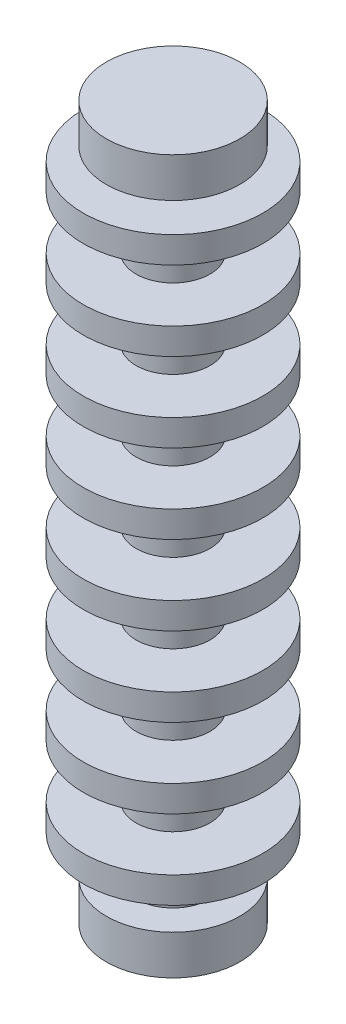
SolidWorks part; units mm, degrees
ref_plane "Front Plane" through (0, 0, 0) normal (0, 0, 1) x (1, 0, 0)
ref_plane "Top Plane" through (0, 0, 0) normal (0, 1, 0) x (1, 0, 0)
ref_plane "Right Plane" through (0, 0, 0) normal (1, 0, 0) x (0, 0, -1)
sketch "Sketch1" plane through (0, 0, 0) normal (0, 0, 1) x (1, 0, 0)
  line L0 (0, -24) -> (0, 24) construction
  line L1 (2.8, 24) -> (2.8, 23)
  line L2 (-20.9325, 24) -> (2.8, 24) construction
  line L3 (2.8, 18) -> (2.8, 17)
  line L4 (2.8, 17) -> (6.8, 17)
  line L5 (2.8, 23) -> (6.8, 23)
  line L6 (6.8, 23) -> (6.8, 21)
  line L7 (6.8, 21) -> (2.8, 21)
  line L8 (2.8, 21) -> (2.8, 18)
  line L9 (2.8, 24) -> (5.05, 24)
  line L10 (5.05, 24) -> (5.05, 27)
  line L11 (5.05, 27) -> (0, 27)
  line L12 (0, 0) -> (33.9437, 0) construction
  line L13 (6.8, 17) -> (6.8, 15)
  line L14 (6.8, 15) -> (2.8, 15)
  line L15 (2.8, 15) -> (2.8, 12)
  line L16 (0, 27) -> (0, -27)
  line L17 (5.05, -27) -> (0, -27)
  line L18 (5.05, -24) -> (5.05, -27)
  line L19 (2.8, -24) -> (5.05, -24)
  line L20 (2.8, 12) -> (2.8, 11)
  line L21 (2.8, 11) -> (6.8, 11)
  line L22 (6.8, 11) -> (6.8, 9)
  line L23 (6.8, 9) -> (2.8, 9)
  line L24 (2.8, 9) -> (2.8, 6)
  line L29 (2.8, 6) -> (2.8, 5)
  line L30 (2.8, 5) -> (6.8, 5)
  line L31 (6.8, 5) -> (6.8, 3)
  line L32 (6.8, 3) -> (2.8, 3)
  line L33 (2.8, 3) -> (2.8, 0)
  line L38 (2.8, 0) -> (2.8, -1)
  line L39 (2.8, -1) -> (6.8, -1)
  line L40 (6.8, -1) -> (6.8, -3)
  line L41 (6.8, -3) -> (2.8, -3)
  line L42 (2.8, -3) -> (2.8, -6)
  line L47 (2.8, -6) -> (2.8, -7)
  line L48 (2.8, -7) -> (6.8, -7)
  line L49 (6.8, -7) -> (6.8, -9)
  line L50 (6.8, -9) -> (2.8, -9)
  line L51 (2.8, -9) -> (2.8, -12)
  line L56 (2.8, -12) -> (2.8, -13)
  line L57 (2.8, -13) -> (6.8, -13)
  line L58 (6.8, -13) -> (6.8, -15)
  line L59 (6.8, -15) -> (2.8, -15)
  line L60 (2.8, -15) -> (2.8, -18)
  line L65 (2.8, -18) -> (2.8, -19)
  line L66 (2.8, -19) -> (6.8, -19)
  line L67 (6.8, -19) -> (6.8, -21)
  line L68 (6.8, -21) -> (2.8, -21)
  line L69 (2.8, -21) -> (2.8, -24)
  point P4 (0, 0)
  dimension "D1" = 48
  dimension "D2" = 2.8
  dimension "D3" = 5.05
  dimension "D4" = 3
  dimension "D7" = 2
  dimension "D11" = 4
  dimension "D12" = 8
revolve "Revolve1" add sketch "Sketch1" angle 360 about L16
